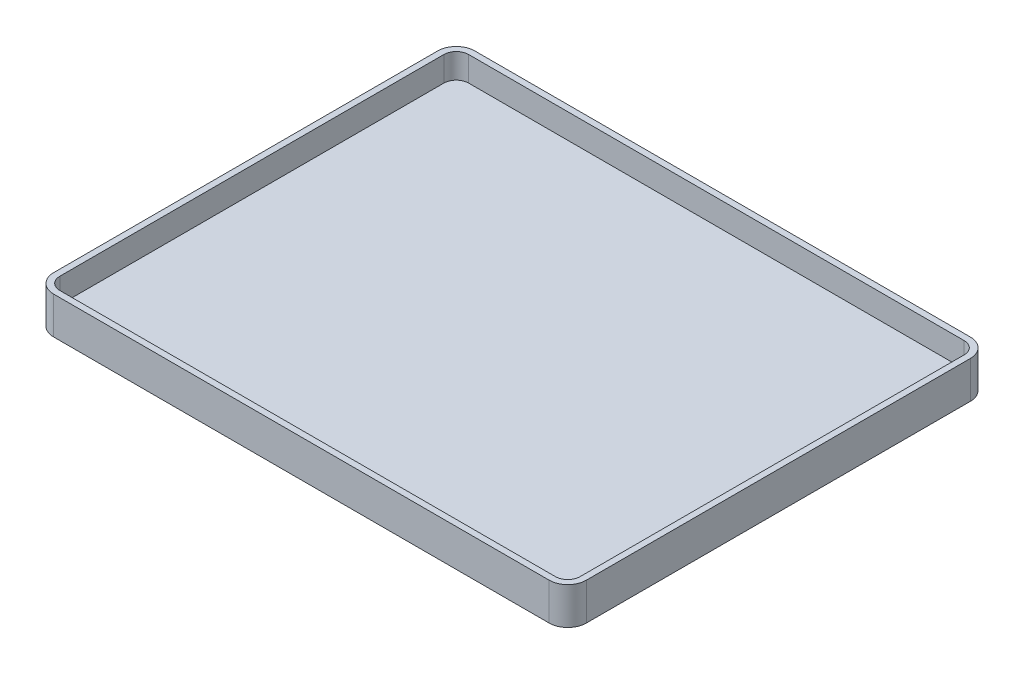
SolidWorks part; units mm, degrees
ref_plane "Front Plane" through (0, 0, 0) normal (0, 0, 1) x (1, 0, 0)
ref_plane "Top Plane" through (0, 0, 0) normal (0, 1, 0) x (1, 0, 0)
ref_plane "Right Plane" through (0, 0, 0) normal (1, 0, 0) x (0, 0, -1)
sketch "Sketch1" plane through (0, 0, 0) normal (0, 1, 0) x (1, 0, 0)
  line L1 (0, 0) -> (273.05, 0)
  line L2 (0, 0) -> (0, 215.9)
  line L3 (0, 215.9) -> (273.05, 215.9)
  line L4 (273.05, 0) -> (273.05, 215.9)
  dimension "D1" = 273.05
  dimension "D2" = 215.9
extrude "Boss-Extrude1" add sketch "Sketch1" along normal blind 19.05
fillet "Fillet1" radius 9.525 4 edges at (273.05, 9.525, 0) (273.05, 9.525, -215.9) (0, 9.525, 0) (0, 9.525, -215.9)
sketch "Sketch3" plane through (0, 19.05, 0) normal (0, 1, 0) x (1, 0, 0)
  line L25 (269.875, 9.525) -> (269.875, 206.375)
  line L26 (9.525, 3.175) -> (263.525, 3.175)
  line L27 (3.175, 206.375) -> (3.175, 9.525)
  line L28 (263.525, 212.725) -> (9.525, 212.725)
  line L29 (269.875, 9.525) -> (269.875, 206.375)
  line L30 (9.525, 3.175) -> (263.525, 3.175)
  line L31 (3.175, 206.375) -> (3.175, 9.525)
  line L32 (263.525, 212.725) -> (9.525, 212.725)
  arc A21 (269.875, 206.375) -> (263.525, 212.725) centre (263.525, 206.375) ccw
  arc A22 (263.525, 3.175) -> (269.875, 9.525) centre (263.525, 9.525) ccw
  arc A23 (3.175, 9.525) -> (9.525, 3.175) centre (9.525, 9.525) ccw
  arc A24 (9.525, 212.725) -> (3.175, 206.375) centre (9.525, 206.375) ccw
  arc A25 (269.875, 206.375) -> (263.525, 212.725) centre (263.525, 206.375) ccw
  arc A26 (263.525, 3.175) -> (269.875, 9.525) centre (263.525, 9.525) ccw
  arc A27 (3.175, 9.525) -> (9.525, 3.175) centre (9.525, 9.525) ccw
  arc A28 (9.525, 212.725) -> (3.175, 206.375) centre (9.525, 206.375) ccw
  dimension "D1" = 3.175
extrude "Cut-Extrude1" cut sketch "Sketch3" against normal blind 12.7
